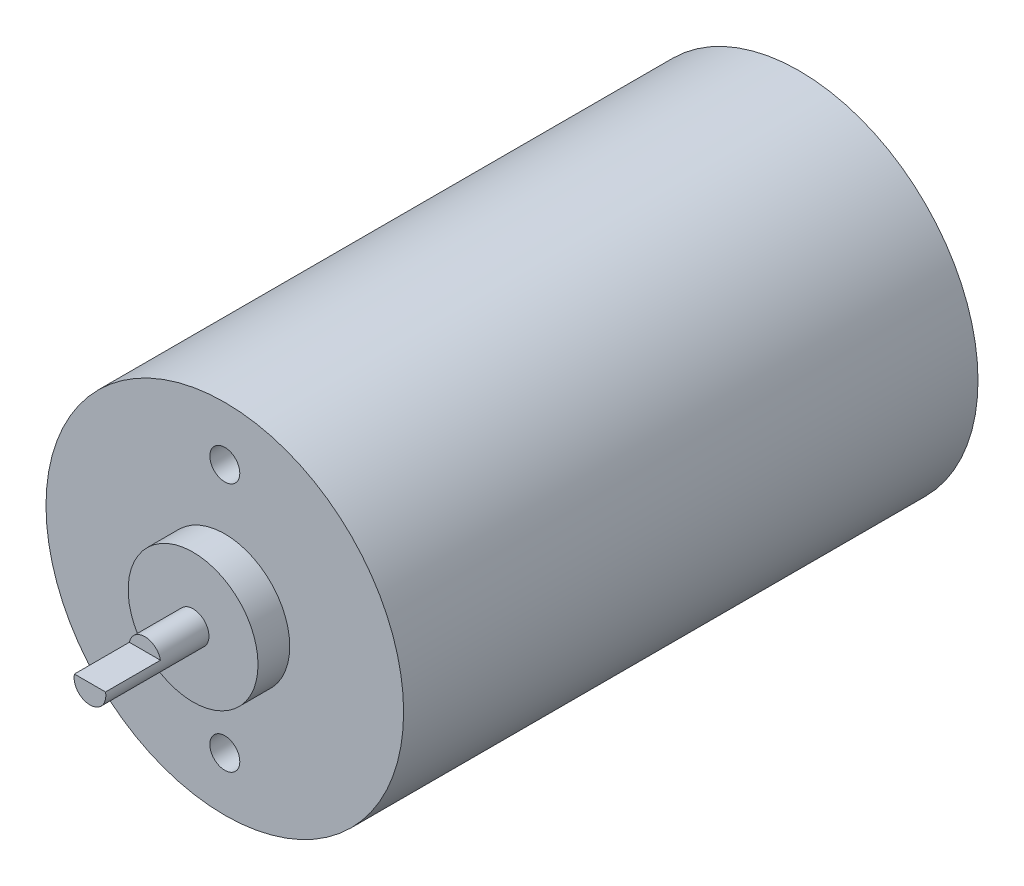
SolidWorks part; units mm, degrees
ref_plane "Front Plane" through (0, 0, 0) normal (0, 0, 1) x (1, 0, 0)
ref_plane "Top Plane" through (0, 0, 0) normal (0, 1, 0) x (1, 0, 0)
ref_plane "Right Plane" through (0, 0, 0) normal (1, 0, 0) x (0, 0, -1)
sketch "Sketch1" plane through (0, 0, 0) normal (0, 0, 1) x (1, 0, 0)
  circle A0 centre (0, 0) radius 17.9
  dimension "D1" = 35.8
extrude "Boss-Extrude1" add sketch "Sketch1" along normal blind 57.5
sketch "Sketch2" plane through (0, 0, 57.5) normal (0, 0, 1) x (1, 0, 0)
  circle A0 centre (0, 0) radius 6.5
  dimension "D1" = 13
extrude "Boss-Extrude2" add sketch "Sketch2" along normal blind 3.175
sketch "Sketch3" plane through (0, 0, 60.675) normal (0, 0, 1) x (1, 0, 0)
  circle A0 centre (0, 0) radius 1.5875
  dimension "D1" = 3.175
extrude "Boss-Extrude3" add sketch "Sketch3" along normal blind 10.325
sketch "Sketch4" plane through (0, 0, 71) normal (0, 0, 1) x (1, 0, 0)
  line L0 (-1.5551, 0.3193) -> (1.5551, 0.3193)
  circle A0 centre (0, 0) radius 1.5875 construction
  arc A1 (-1.5551, 0.3193) -> (1.5551, 0.3193) centre (0, 0.0193) cw
  dimension "D1" = 0.3
extrude "Cut-Extrude1" cut sketch "Sketch4" against normal blind 5.5
sketch "Sketch5" plane through (0, 0, 57.5) normal (0, 0, 1) x (1, 0, 0)
  circle A0 centre (0, 0) radius 12.5 construction
  circle A1 centre (0, 12.5) radius 1.5
  circle A2 centre (0, -12.5) radius 1.5
  dimension "D1" = 25
  dimension "D2" = 3
extrude "Cut-Extrude2" cut sketch "Sketch5" against normal blind 5.5
